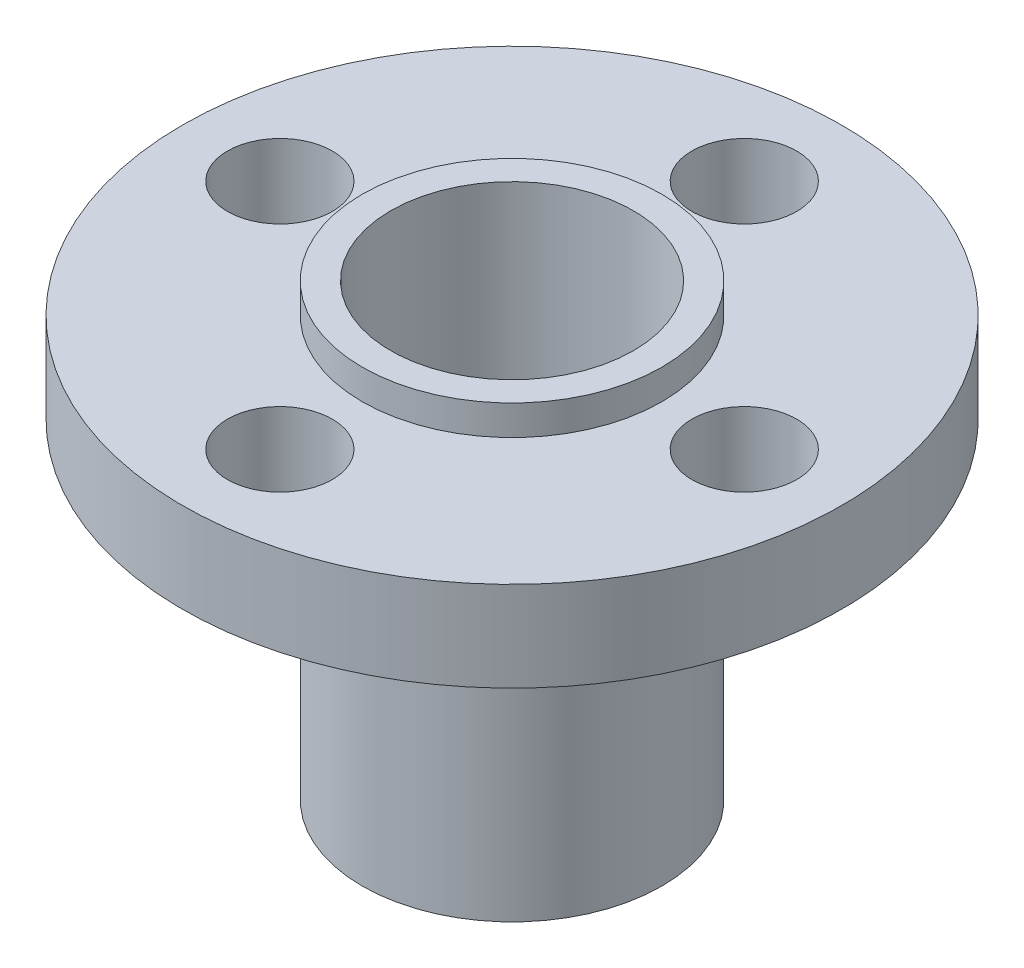
SolidWorks part; units mm, degrees
ref_plane "Ön Düzlem" through (0, 0, 0) normal (0, 0, 1) x (1, 0, 0)
ref_plane "Üst Düzlem" through (0, 0, 0) normal (0, 1, 0) x (1, 0, 0)
ref_plane "Sağ Düzlem" through (0, 0, 0) normal (1, 0, 0) x (0, 0, -1)
sketch "Çizim1" plane through (0, 0, 0) normal (0, 0, 1) x (1, 0, 0)
  line L0 (0, 6.5729) -> (0, -8.4271) construction
  line L1 (0, 6.5729) -> (5, 6.5729)
  line L2 (5, 6.5729) -> (5, 5.5729)
  line L3 (5, 5.5729) -> (11, 5.5729)
  line L4 (11, 5.5729) -> (11, 2.5729)
  line L5 (11, 2.5729) -> (5, 2.5729)
  line L6 (5, 2.5729) -> (5, -8.4271)
  line L7 (5, -8.4271) -> (0, -8.4271)
  line L8 (0, 6.5729) -> (0, -8.4271)
  dimension "D1" = 11
  dimension "D2" = 1
  dimension "D3" = 5
  dimension "D4" = 3
  dimension "D5" = 6
  dimension "D6" = 15
revolve "Döndür1" add sketch "Çizim1" angle 360 about L0
sketch "Çizim2" plane through (0, 6.5729, 0) normal (0, 1, 0) x (1, 0, 0)
  circle A0 centre (0, 0) radius 4.05
  dimension "D1" = 8.1
extrude "Kes-Ekstrüzyon1" cut sketch "Çizim2" against normal up to next
sketch "Çizim3" plane through (0, 5.5729, 0) normal (0, 1, 0) x (1, 0, 0)
  circle A0 centre (0, 7.75) radius 1.75
  circle A1 centre (7.75, 0) radius 1.75
  circle A2 centre (0, -7.75) radius 1.75
  circle A3 centre (-7.75, 0) radius 1.75
  point P12 (0, 0)
  dimension "D1" = 3.5
  dimension "D2" = 7.75
  dimension "D4" = 15.5
  dimension "D3" = 4
extrude "Kes-Ekstrüzyon2" cut sketch "Çizim3" against normal up to next
